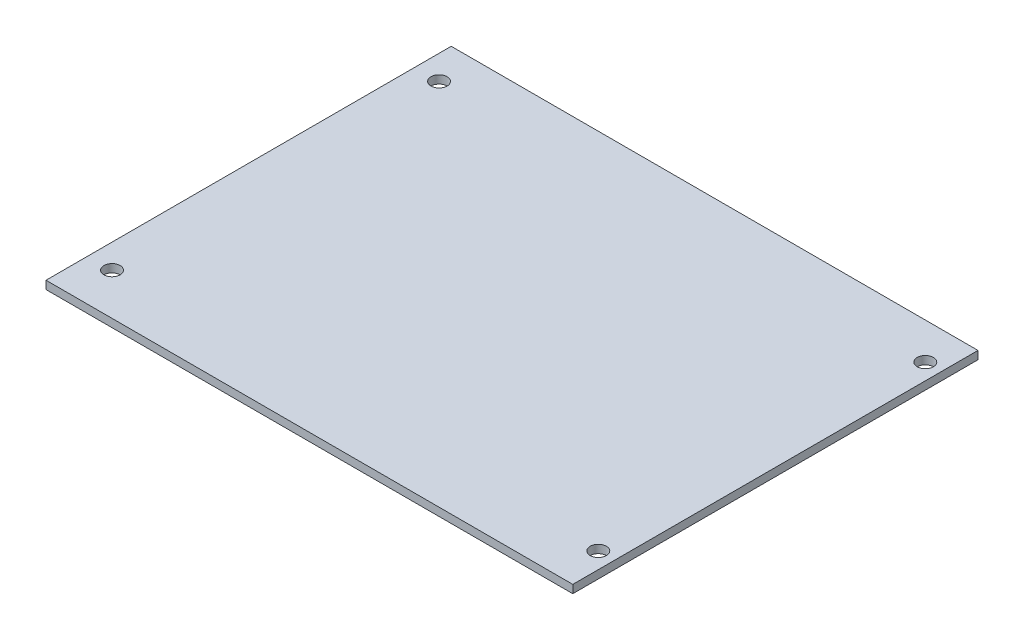
SolidWorks part; units mm, degrees
ref_plane "Front Plane" through (0, 0, 0) normal (0, 0, 1) x (1, 0, 0)
ref_plane "Top Plane" through (0, 0, 0) normal (0, 1, 0) x (1, 0, 0)
ref_plane "Right Plane" through (0, 0, 0) normal (1, 0, 0) x (0, 0, -1)
sketch "Sketch1" plane through (0, 0, 0) normal (0, 1, 0) x (1, 0, 0)
  line L0 (256.773, 592.6688) -> (1283.8649, 592.6688) construction
  line L2 (0, 0) -> (130, 0)
  line L3 (0, 0) -> (0, 100)
  line L4 (0, 100) -> (130, 100)
  line L5 (130, 0) -> (130, 100)
  circle A0 centre (6, 10.3) radius 2
  circle A1 centre (126, 10.3) radius 2
  circle A2 centre (126, 91) radius 2
  circle A3 centre (6, 91) radius 2
  point P17 (0, 0)
extrude "Boss-Extrude1" add sketch "Sketch1" along normal blind 2
